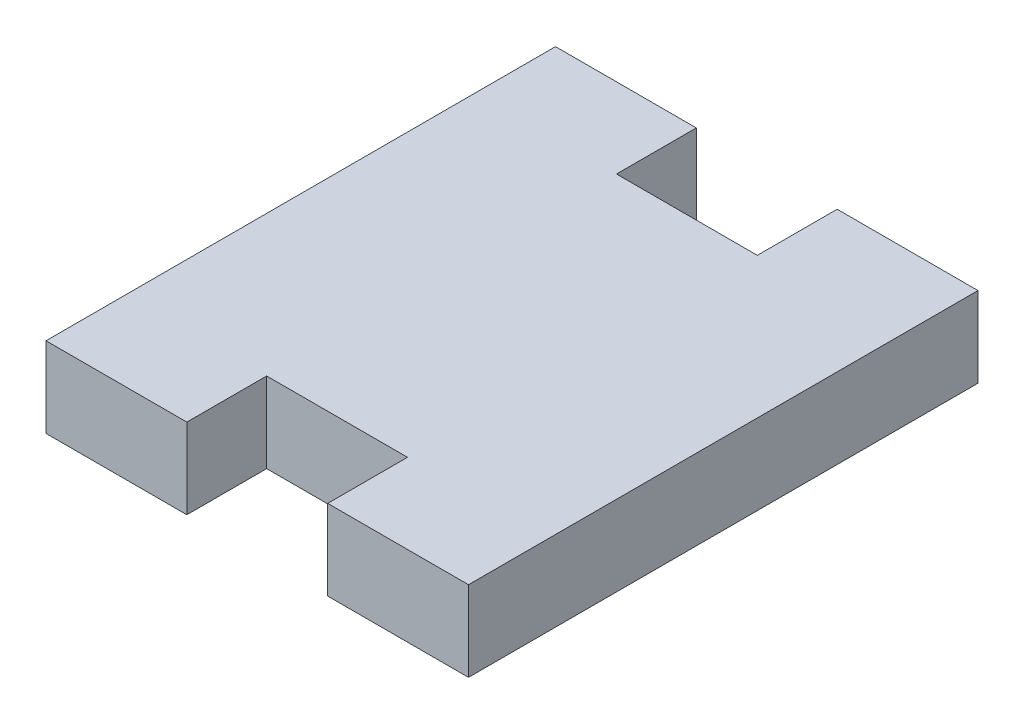
SolidWorks part; units mm, degrees
ref_plane "Front Plane" through (0, 0, 0) normal (0, 0, 1) x (1, 0, 0)
ref_plane "Top Plane" through (0, 0, 0) normal (0, 1, 0) x (1, 0, 0)
ref_plane "Right Plane" through (0, 0, 0) normal (1, 0, 0) x (0, 0, -1)
sketch "Sketch1" plane through (0, 0, 0) normal (0, 1, 0) x (1, 0, 0)
  line L1 (0, 0) -> (50.8, 0)
  line L2 (0, 0) -> (0, 50.8)
  line L3 (0, 50.8) -> (50.8, 50.8)
  line L4 (50.8, 0) -> (50.8, 50.8)
  line L5 (0, 0) -> (50.8, 50.8) construction
  line L6 (0, 50.8) -> (50.8, 0) construction
  point P4 (25.4, 25.4)
  dimension "D1" = 50.8
  dimension "D2" = 50.8
extrude "Boss-Extrude1" add sketch "Sketch1" along normal blind 4.826
sketch "Sketch2" plane through (0, 0, 0) normal (0, -1, 0) x (1, 0, 0)
  line L0 (20.58, -30.63) -> (45.98, -30.63) construction
  line L1 (20.58, -30.63) -> (45.98, -30.63) construction
  line L2 (0, -50.8) -> (0, 0) construction
  line L3 (50.8, -50.8) -> (0, -50.8)
  line L4 (50.8, -50.8) -> (50.8, -30.63)
  line L5 (50.8, -30.63) -> (0, -30.63)
  line L6 (0, -50.8) -> (0, -30.63)
  line L7 (50.8, -50.8) -> (0, -30.63) construction
  line L8 (50.8, -30.63) -> (0, -50.8) construction
  point P6 (25.4, -40.715)
extrude "Cut-Extrude1" cut sketch "Sketch2" against normal through all
sketch "Sketch3" plane through (0, 0, 0) normal (0, -1, 0) x (1, 0, 0)
  line L1 (0, 0) -> (50.8, 0) construction
  line L10 (0, -30.63) -> (25.4, -30.63)
  line L11 (0, -30.63) -> (0, 0)
  line L12 (0, 0) -> (25.4, 0)
  line L13 (25.4, -30.63) -> (25.4, 0)
  line L14 (0, -30.63) -> (25.4, 0) construction
  line L15 (0, 0) -> (25.4, -30.63) construction
  point P4 (12.7, -15.315)
extrude "Cut-Extrude2" cut sketch "Sketch3" against normal through all
sketch "Sketch4" plane through (0, 4.826, 0) normal (0, 1, 0) x (1, 0, 0)
  line L0 (25.4, 0) -> (50.8, 0) construction
  line L1 (33.8667, 0) -> (42.3333, 0)
  line L2 (33.8667, 0) -> (33.8667, 4.8)
  line L3 (33.8667, 4.8) -> (42.3333, 4.8)
  line L4 (42.3333, 0) -> (42.3333, 4.8)
  line L5 (33.8667, 0) -> (42.3333, 4.8) construction
  line L6 (33.8667, 4.8) -> (42.3333, 0) construction
  line L7 (25.4, 30.63) -> (33.8667, 30.63) construction
  line L8 (50.8, 0) -> (42.3333, 0) construction
  line L9 (50.8, 30.63) -> (25.4, 30.63) construction
  line L10 (33.8667, 30.63) -> (42.3333, 30.63)
  line L11 (33.8667, 30.63) -> (33.8667, 25.83)
  line L12 (33.8667, 25.83) -> (42.3333, 25.83)
  line L13 (42.3333, 30.63) -> (42.3333, 25.83)
  line L14 (33.8667, 30.63) -> (42.3333, 25.83) construction
  line L15 (33.8667, 25.83) -> (42.3333, 30.63) construction
  line L16 (42.3333, 30.63) -> (50.8, 30.63) construction
  line L17 (25.4, 0) -> (33.8667, 0) construction
  line L18 (50.8, 0) -> (42.3333, 0) construction
  point P4 (38.1, 2.4)
  point P15 (38.1, 28.23)
  dimension "D2" = 4.8
  dimension "D1" = 4.8
extrude "Cut-Extrude3" cut sketch "Sketch4" against normal through all
equation "\"MDF\"= 4.8mm"
equation "\"Foamcore\"= 4.6mm"
equation "\"GMaterial\"= \"MDF\""
equation "\"PCB\" = 1.6mm"
equation "\"BaseWidth\" = 10in"
equation "\"SkidLength\" = 1in"
equation "\"SkidClearance\" = 0.4in"
equation "\"MotorMountLength\" = 2in"
equation "\"MotorMountWidth\" = \"GMaterial\""
equation "\"MotorMountHeight\" = 2.25in"
equation "\"UnoStackWidth\" = 77.4mm"
equation "\"UnoStackLength\" = 79.8mm"
equation "\"UnoStackHeight\" = 34.2mm"
equation "\"TallHexRiserHeight\" = 22.2mm"
equation "\"PingPongBallSize\" = 40mm"
equation "\"BarrelLength\" = 9in"
equation "\"BarrelSize\" = \"PingPongBallSize\""
equation "\"PlatformLength\" = 4in"
equation "\"PlatformWidth\" = 6in"
equation "\"WheelDiameter\"=2.99213"
equation "\"ServoMountHeight\"=2.49223"
equation "\"ServoGearHeight\" = 0.95330261in"
equation "\"ServoMountLength\"= 1.53774"
equation "\"PivotHoleRadius\"= 0.616358"
equation "\"PlatformMountHeight\" = 3.19"
equation "\"TensionOffSet\"= .3mm"
equation "\"MotorMountWedge\"=0.333333"
equation "\"LaserCutterOffset\"= .3mm"
equation "\"BumperWidth\"=11"
equation "\"PitcherWheelCompression\" = 2.5mm"
equation "\"PitchingWheelWidth\" = 26.2mm"
equation "\"PitchingWheelDiameter\" = 65.5mm"
equation "\"PitchingWheelMountOffset\" = 8.4mm"
equation "\"PitchingWheelInnerDiameter\" = 45.5mm"
equation "\"PitchingWheelBoltShoulder\" = 4.5mm"
equation "\"BrassCouplingLength\" = 18mm"
equation "\"PitchingMotorHeight\" = 57.0mm"
equation "\"PitchingMotorShaftTopHeight\" = \"PitchingMotorHeight\" - 44.1mm"
equation "\"PitchingMotorBodyHeight\" = 38mm"
equation "\"PitchingMotorTopShoulderHeight\" = 40.6mm - \"PitchingMotorBodyHeight\" "
equation "\"PitchingMotorBottomShoulderHeight\" = 40.2mm - \"PitchingMotorBodyHeight\""
equation "\"PitchingMotorBottomShaftHeight\" = \"PitchingMotorHeight\" - \"PitchingMotorShaftTopHeight\" - \"PitchingMotorTopShoulderHeight\" - \"PitchingMotorBodyHeight\" - \"PitchingMotorBottomShoulderHeight\""
equation "\"PitchingMotorShaftDiameter\" = 2.2mm"
equation "\"PitchingMotorBodyDiameter\" = 27.4mm"
equation "\"PitchingMotorTopShoulderDiameter\" = 9.8mm"
equation "\"PitchingMotorBottomShoulderDiameter\" = 9.8mm"
equation "\"BrassCouplingHexSize\" = 12mm"
equation "\"BrassCouplingBoreSize\" = 3.17mm"
equation "\"PitchingMotorMountingHoleDistance\" = 16mm"
equation "\"Acrylic\" = 4.4mm"
equation "\"PitchingMotorDistance\" = \"PitchingWheelDiameter\" + \"PingPongBallSize\" - \"PitcherWheelCompression\"*2"
equation "\"PitchingMotorPlatformOffset\"=1"
equation "\"ServoPlatformOffset\"=1.64173"
equation "\"BallBearingDiameter\" = 22mm"
equation "\"BallBearingWidth\" = 9mm"
equation "\"BallBearingHexShoulder\" = 9mm - 5.9mm"
equation "\"BallBearingHexSize\" = .36in"
equation "\"PlatformMountFootLength\"=0.857143"
equation "\"WheelWidth\"= 26mm"
equation "\"ServoMountReductionBackHeight\"=2.25"
equation "\"PlatformBottomWidthThird\" =  0.857143in"
equation "\"PlatformMountBackReductionHeight\"= 2.5in"
equation "\"PlatformMountBackReductionWidth\"= 3/7in"
equation "\"PlatformMountFrontReductionWidth\" =  1.46226in"
equation "\"PlatformMountFrontReductionHeight\" = 2.5in"
equation "\"D2@Sketch4\"=\"MDF\""
equation "\"D1@Sketch4\"=\"MDF\""
